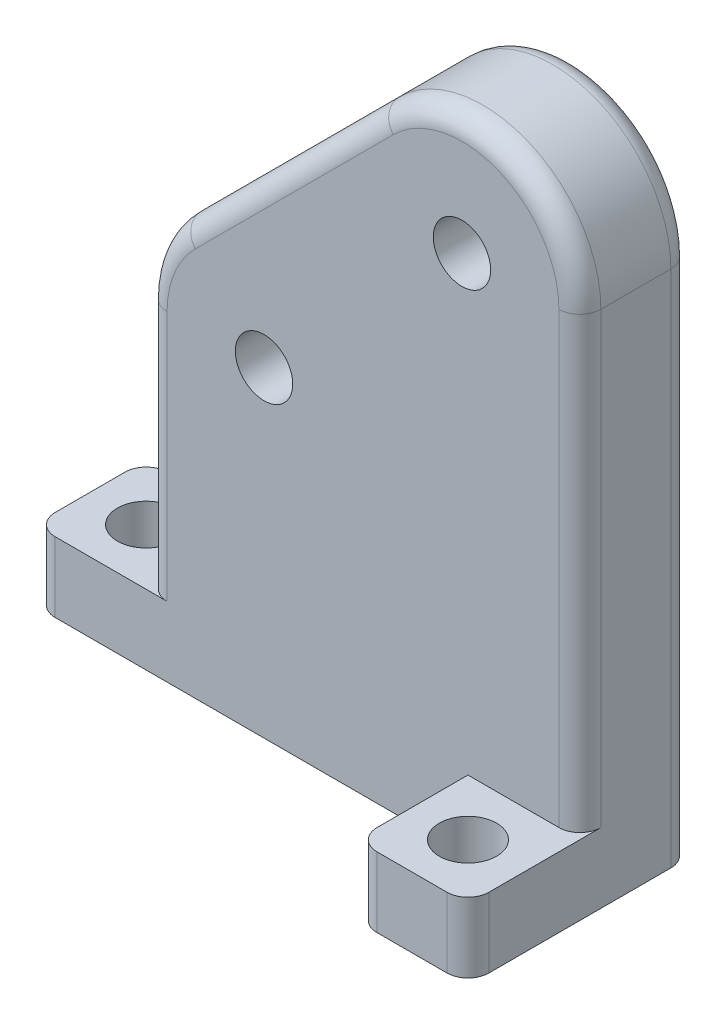
SolidWorks part; units mm, degrees
ref_plane "Plan de face" through (0, 0, 0) normal (0, 0, 1) x (1, 0, 0)
ref_plane "Plan de dessus" through (0, 0, 0) normal (0, 1, 0) x (1, 0, 0)
ref_plane "Plan de droite" through (0, 0, 0) normal (1, 0, 0) x (0, 0, -1)
sketch "Esquisse7" plane through (0, 0, 0) normal (0, 0, 1) x (1, 0, 0)
  line L0 (0, 0) -> (39, 0)
  line L2 (0, 0) -> (0, 5)
  line L3 (0, 5) -> (8, 5)
  line L6 (0, 0) -> (117.5195, 0) construction
  line L8 (8, 5) -> (8, 43.0312) construction
  line L9 (8, 43.0312) -> (24.6109, 43.0312) construction
  line L10 (8, 30) -> (39, 30) construction
  line L11 (8, 5) -> (8, 0) construction
  line L12 (23.5, 30) -> (23.5, 0) construction
  line L13 (23.5, 30) -> (5.8533, 12.3533) construction
  line L14 (23.5, 30) -> (6.9688, 46.5312) construction
  line L15 (39, 0) -> (39, 37.0711)
  line L17 (8, 5) -> (8, 22.9289)
  line L18 (10.4688, 28.8891) -> (24.6109, 43.0312)
  line L19 (-0.6421, 45.5) -> (47.255, 45.5) construction
  circle A0 centre (16.4289, 22.9289) radius 2.05
  circle A1 centre (30.5711, 37.0711) radius 2.05
  circle A2 centre (30.5711, 37.0711) radius 8.4289 construction
  arc A3 (24.6109, 43.0312) -> (39, 37.0711) centre (30.5711, 37.0711) cw
  circle A4 centre (16.4289, 22.9289) radius 8.4289 construction
  arc A5 (10.4688, 28.8891) -> (8, 22.9289) centre (16.4289, 22.9289) ccw
  dimension "D1" = 5
  dimension "D3" = 31
  dimension "D7" = 4.1
  dimension "D4" = 16.8579
  dimension "D2" = 8
  dimension "D5" = 45
  dimension "D6" = 30
  dimension "D8" = 45
  dimension "D9" = 45
  dimension "D10" = 10
extrude "Boss.-Extru.1" add sketch "Esquisse7" along normal blind 8
sketch "Esquisse8" plane through (0, 0, 8) normal (0, 0, 1) x (1, 0, 0)
  line L0 (39, 5) -> (31, 5)
  line L1 (31, 5) -> (31, 0)
  line L6 (0, 5) -> (0, 0)
  line L7 (0, 0) -> (39, 0)
  line L8 (39, 0) -> (39, 37.0711)
  line L9 (24.6109, 43.0312) -> (10.4688, 28.8891)
  line L10 (8, 22.9289) -> (8, 5)
  line L11 (8, 5) -> (0, 5)
  line L12 (0, 5) -> (0, 0)
  line L13 (0, 0) -> (39, 0)
  line L14 (39, 0) -> (39, 37.0711)
  line L16 (8, 22.9289) -> (8, 5)
  line L17 (8, 5) -> (0, 5)
  line L20 (24.6109, 43.0312) -> (10.4688, 28.8891)
  arc A3 (39, 37.0711) -> (24.6109, 43.0312) centre (30.5711, 37.0711) ccw
  arc A4 (10.4688, 28.8891) -> (8, 22.9289) centre (16.4289, 22.9289) ccw
  arc A6 (39, 37.0711) -> (24.6109, 43.0312) centre (30.5711, 37.0711) ccw
  arc A7 (10.4688, 28.8891) -> (8, 22.9289) centre (16.4289, 22.9289) ccw
  line M14 (0, 0) -> (39, 0)
  line M15 (39, 0) -> (39, 37.0711)
  dimension "D2" = 5
  dimension "D3" = 8
  dimension "D1" = 0
extrude "Boss.-Extru.2" add sketch "Esquisse8" along normal blind 8 contours L0 L1 M14 M15
sketch "Esquisse9" plane through (0, 5, 0) normal (0, 1, 0) x (1, 0, 0)
  line L0 (0, -4) -> (8, -4) construction
  line L1 (35, -8) -> (35, -16) construction
  line L2 (31, -12) -> (39, -12) construction
  line L3 (4, 0) -> (4, -8) construction
  line L4 (8, 0) -> (0, 0)
  line L5 (0, 0) -> (0, -8)
  line L6 (0, -8) -> (8, -8)
  line L7 (8, -8) -> (8, 0)
  line L8 (8, 0) -> (0, 0)
  line L9 (0, 0) -> (0, -8)
  line L10 (0, -8) -> (8, -8)
  line L12 (39, -8) -> (31, -8)
  line L13 (31, -8) -> (31, -16)
  line L14 (31, -16) -> (39, -16)
  line L15 (39, -16) -> (39, -8)
  line L16 (39, -8) -> (31, -8)
  line L17 (31, -8) -> (31, -16)
  line L18 (31, -16) -> (39, -16)
  line L19 (39, -16) -> (39, -8)
  line L24 (8, -8) -> (8, 0)
  circle A0 centre (35, -12) radius 2.05
  circle A1 centre (4, -4) radius 2.05
  dimension "D3" = 4.1
  dimension "D8" = 35
  dimension "D4" = 4
  dimension "D5" = 4
  dimension "D6" = 12
  dimension "D7" = 4
  dimension "D1" = 0
  dimension "D2" = 0
extrude "Enlèv. mat.-Extru.3" cut sketch "Esquisse9" against normal through all both and the other way through all contours A1 | A0
fillet "Congé5" radius 1.5 14 edges at (39, 18.5355, 0) (33.7967, 44.8584, 0) (8.6416, 26.1545, 0) (39, 21.0355, 8) (33.7967, 44.8584, 8) (8.6416, 26.1545, 8) (0, 2.5, 0) (0, 2.5, 8) (31, 2.5, 16) (39, 2.5, 16) (8, 13.9645, 0) (8, 13.9645, 8) (17.5398, 35.9602, 8) (17.5398, 35.9602, 0)
